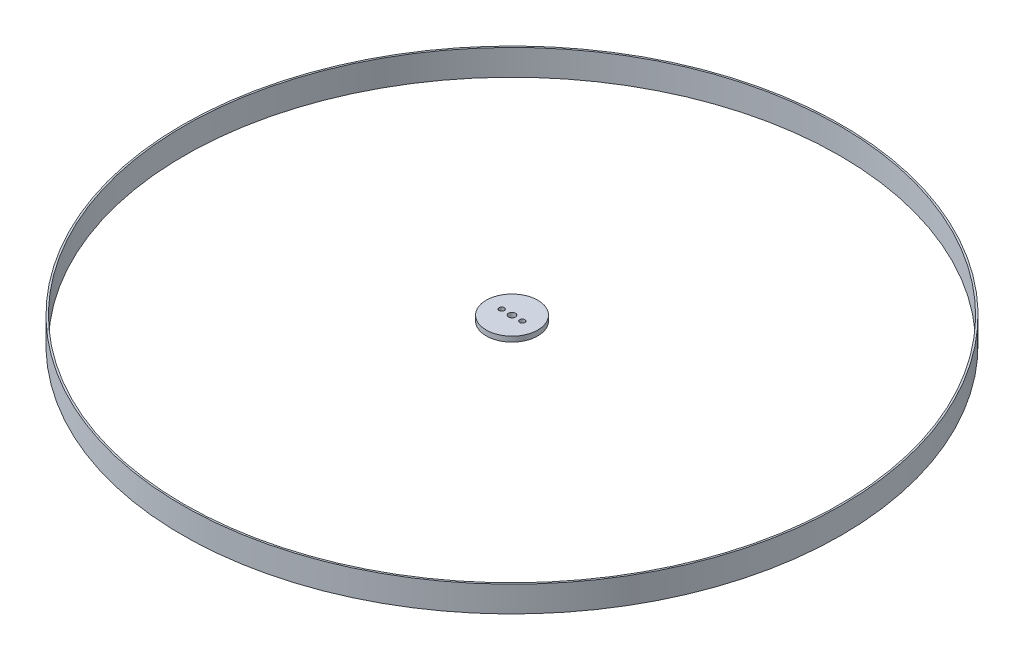
SolidWorks part; units mm, degrees
ref_plane "Front Plane" through (0, 0, 0) normal (0, 0, 1) x (1, 0, 0)
ref_plane "Top Plane" through (0, 0, 0) normal (0, 1, 0) x (1, 0, 0)
ref_plane "Right Plane" through (0, 0, 0) normal (1, 0, 0) x (0, 0, -1)
sketch "Sketch1" plane through (0, 0, 0) normal (0, 1, 0) x (1, 0, 0)
  circle A0 centre (0, 0) radius 2
  circle A2 centre (6, 0) radius 1.5
  circle A3 centre (-6, 0) radius 1.5
  circle A5 centre (0, 0) radius 15
  point P11 (0, 0)
  dimension "D1" = 2
extrude "Boss-Extrude1" add sketch "Sketch1" along normal blind 3 contours A5 A3 A2 A0
sketch "Sketch3" plane through (0, 3, 0) normal (0, 1, 0) x (1, 0, 0)
  circle A0 centre (0, 0) radius 190.5
extrude "Extrude-Thin3" add sketch "Sketch3" against normal blind 15 separate body thin
